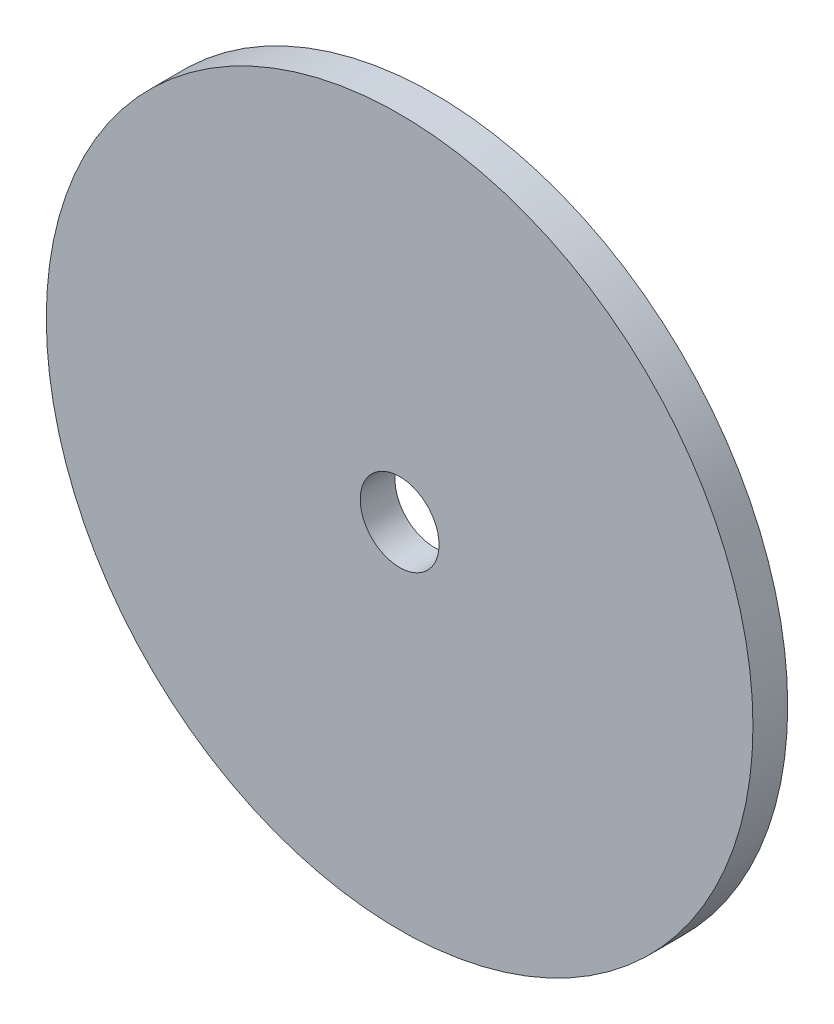
SolidWorks part; units mm, degrees
material "Acrylic (Medium-high impact)"
ref_plane "Front Plane" through (0, 0, 0) normal (0, 0, 1) x (1, 0, 0)
ref_plane "Top Plane" through (0, 0, 0) normal (0, 1, 0) x (1, 0, 0)
ref_plane "Right Plane" through (0, 0, 0) normal (1, 0, 0) x (0, 0, -1)
sketch "Model" plane through (0, 0, 0) normal (0, 0, 1) x (1, 0, 0)
  circle A0 centre (0, 0) radius 30.5
  circle A1 centre (0, 0) radius 3.4
  dimension "D1" = 6.8
  dimension "D2" = 61
extrude "Boss-Extrude1" add sketch "Model" along normal blind 3
